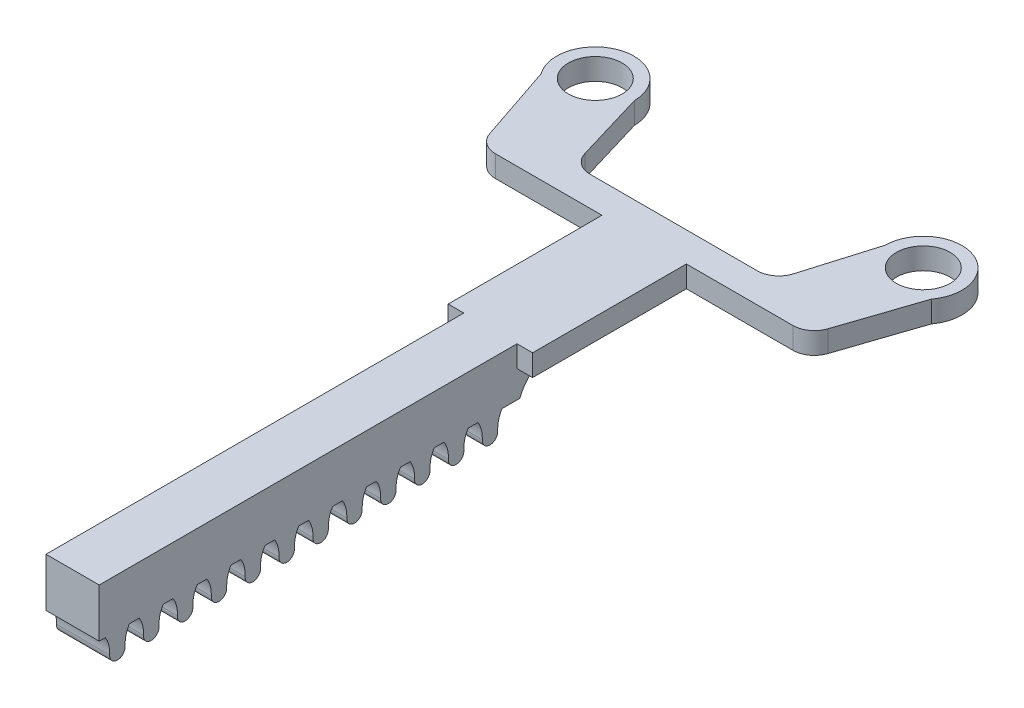
SolidWorks part; units mm, degrees
ref_plane "Front Plane" through (0, 0, 0) normal (0, 0, 1) x (1, 0, 0)
ref_plane "Top Plane" through (0, 0, 0) normal (0, 1, 0) x (1, 0, 0)
ref_plane "Right Plane" through (0, 0, 0) normal (1, 0, 0) x (0, 0, -1)
sketch "Sketch1" plane through (0, 0, 0) normal (0, 1, 0) x (1, 0, 0)
  line L0 (-0.29, 2.86) -> (-2.27, 2.86)
  line L1 (0.99, 0) -> (0.99, -7.77)
  line L2 (0, 0) -> (0, -7.77)
  line L3 (0, -7.77) -> (0.99, -7.77)
  line L4 (0.495, 0) -> (0.495, -7.77)
  line L5 (-0.29, 3.41) -> (1.28, 3.41)
  line L6 (-0.29, 2.86) -> (-0.29, 0)
  line L7 (-0.29, 0) -> (0, 0)
  line L8 (0.495, 3.41) -> (0.495, 0)
  line L9 (-0.29, 3.41) -> (0.495, 3.41)
  line L10 (1.28, 0) -> (0.99, 0)
  line L11 (1.28, 2.86) -> (1.28, 0)
  line L12 (0.495, 3.41) -> (0.495, 2.86)
  line L13 (-0.29, 3.41) -> (-1.06, 3.41)
  line L14 (1.28, 3.41) -> (2.05, 3.41)
  line L15 (-1.4433, 3.6956) -> (-1.8351, 5.0084)
  line L16 (1.28, 2.86) -> (3.26, 2.86)
  line L17 (-2.6491, 3.1324) -> (-3.1341, 4.5729)
  line L18 (3.6391, 3.1324) -> (4.1241, 4.5729)
  line L19 (2.4333, 3.6956) -> (2.8251, 5.0084)
  circle A0 centre (-2.5551, 5.0011) radius 0.5
  arc A1 (-1.8351, 5.0084) -> (-3.1341, 4.5729) centre (-2.5551, 5.0011) ccw
  arc A2 (-2.6491, 3.1324) -> (-2.27, 2.86) centre (-2.27, 3.26) ccw
  arc A3 (-1.4433, 3.6956) -> (-1.06, 3.41) centre (-1.06, 3.81) ccw
  arc A4 (2.4333, 3.6956) -> (2.05, 3.41) centre (2.05, 3.81) cw
  arc A5 (3.6391, 3.1324) -> (3.26, 2.86) centre (3.26, 3.26) cw
  arc A6 (2.8251, 5.0084) -> (4.1241, 4.5729) centre (3.5451, 5.0011) cw
  circle A7 centre (3.5451, 5.0011) radius 0.5
  point P16 (0, 0)
  point P17 (0, 0)
  dimension "D6" = 1.98
  dimension "D8" = 1.37
  dimension "D9" = 1.52
  dimension "D10" = 2.16
  dimension "D1" = 0.785
  dimension "D2" = 7.77
  dimension "D3" = 0.495
  dimension "D4" = 3.41
  dimension "D7" = 0.77
  dimension "D11" = 0.72
extrude "Boss-Extrude1" add sketch "Sketch1" along normal blind 0.4 contours A6 L19 A4 L14 L5 L8 L4 L3 L1 L10 L11 L16 A5 L18 A7 | A3 L15 A1 L17 A2 L0 L6 L7 L2 L3 L4 L8 L5 L13 A0
sketch "Sketch2" plane through (0, 0, 0) normal (0, -1, 0) x (1, 0, 0)
  line L1 (0.99, 7.77) -> (0, 7.77)
  line L2 (0.99, 7.77) -> (0.99, 0)
  line L3 (0.99, 0) -> (0, 0)
  line L4 (0, 7.77) -> (0, 0)
extrude "Boss-Extrude2" add sketch "Sketch2" along normal blind 1
sketch "Sketch4" plane through (0, 0, 0) normal (-1, 0, 0) x (0, 0, 1)
sketch "Sketch5" plane through (0, 0, 0) normal (-1, 0, 0) x (0, 0, 1)
  line L0 (7.2892, -0.8353) -> (7.2892, -0.4252) construction
  line L1 (7.2081, -0.5054) -> (6.7982, -0.5054)
  line L2 (7.6566, -0.5054) -> (7.7801, -0.5054)
  line L3 (7.0266, -0.5054) -> (7.1501, -0.5054)
  line L4 (6.5781, -0.5054) -> (6.4546, -0.5054)
  line L5 (6.3966, -0.5054) -> (6.5201, -0.5054)
  line L6 (5.9481, -0.5054) -> (5.8246, -0.5054)
  line L7 (5.7666, -0.5054) -> (5.8901, -0.5054)
  line L8 (5.3181, -0.5054) -> (5.1946, -0.5054)
  line L9 (5.1366, -0.5054) -> (5.2601, -0.5054)
  line L10 (4.6881, -0.5054) -> (4.5646, -0.5054)
  line L11 (4.5066, -0.5054) -> (4.6301, -0.5054)
  line L12 (4.0581, -0.5054) -> (3.9346, -0.5054)
  line L13 (3.8766, -0.5054) -> (4.0001, -0.5054)
  line L14 (3.4281, -0.5054) -> (3.3046, -0.5054)
  line L15 (3.2466, -0.5054) -> (3.3701, -0.5054)
  line L16 (2.7981, -0.5054) -> (2.6746, -0.5054)
  line L17 (2.6166, -0.5054) -> (2.7401, -0.5054)
  line L18 (2.1681, -0.5054) -> (2.0446, -0.5054)
  line L19 (1.9866, -0.5054) -> (2.1101, -0.5054)
  line L20 (1.5381, -0.5054) -> (1.4146, -0.5054)
  line L21 (1.3566, -0.5054) -> (1.4801, -0.5054)
  line L22 (0.9081, -0.5054) -> (0.7846, -0.5054)
  line L23 (0.7266, -0.5054) -> (0.8501, -0.5054)
  line L24 (0.2781, -0.5054) -> (0.1546, -0.5054)
  line L25 (7.7801, -0.5054) -> (7.9342, -1.2016)
  line L26 (7.9342, -1.2016) -> (-0.0987, -1.2016)
  line L27 (-0.0987, -1.2016) -> (0.1546, -0.5054)
  circle A0 centre (7.4324, -0.8353) radius 0.1432
  arc A1 (6.6596, -0.8245) -> (6.9451, -0.8245) centre (6.8024, -0.8353) ccw
  arc A2 (6.0296, -0.8245) -> (6.3151, -0.8245) centre (6.1724, -0.8353) ccw
  arc A3 (5.3996, -0.8245) -> (5.6851, -0.8245) centre (5.5424, -0.8353) ccw
  arc A4 (4.7696, -0.8245) -> (5.0551, -0.8245) centre (4.9124, -0.8353) ccw
  arc A5 (4.1396, -0.8245) -> (4.4251, -0.8245) centre (4.2824, -0.8353) ccw
  arc A6 (3.5096, -0.8245) -> (3.7951, -0.8245) centre (3.6524, -0.8353) ccw
  arc A7 (2.8796, -0.8245) -> (3.1651, -0.8245) centre (3.0224, -0.8353) ccw
  arc A8 (2.2496, -0.8245) -> (2.5351, -0.8245) centre (2.3924, -0.8353) ccw
  arc A9 (1.6196, -0.8245) -> (1.9051, -0.8245) centre (1.7624, -0.8353) ccw
  arc A10 (0.9896, -0.8245) -> (1.2751, -0.8245) centre (1.1324, -0.8353) ccw
  arc A11 (0.3596, -0.8245) -> (0.6451, -0.8245) centre (0.5024, -0.8353) ccw
  spline S0 degree 2 poles (7.2892, -0.8353) (7.2977, -0.6466) (7.2081, -0.5054) knots 0 0 0 0.769777 0.769777 0.769777
  spline S1 degree 2 poles (7.5755, -0.8353) (7.567, -0.6466) (7.6566, -0.5054) knots 0 0 0 0.769777 0.769777 0.769777
  spline S2 degree 2 poles (6.6592, -0.8353) (6.6677, -0.6466) (6.5781, -0.5054) knots 0 0 0 0.769777 0.769777 0.769777
  spline S3 degree 2 poles (6.9455, -0.8353) (6.937, -0.6466) (7.0266, -0.5054) knots 0 0 0 0.769777 0.769777 0.769777
  spline S4 degree 2 poles (6.0292, -0.8353) (6.0377, -0.6466) (5.9481, -0.5054) knots 0 0 0 0.769777 0.769777 0.769777
  spline S5 degree 2 poles (6.3155, -0.8353) (6.307, -0.6466) (6.3966, -0.5054) knots 0 0 0 0.769777 0.769777 0.769777
  spline S6 degree 2 poles (5.3992, -0.8353) (5.4077, -0.6466) (5.3181, -0.5054) knots 0 0 0 0.769777 0.769777 0.769777
  spline S7 degree 2 poles (5.6855, -0.8353) (5.677, -0.6466) (5.7666, -0.5054) knots 0 0 0 0.769777 0.769777 0.769777
  spline S8 degree 2 poles (4.7692, -0.8353) (4.7777, -0.6466) (4.6881, -0.5054) knots 0 0 0 0.769777 0.769777 0.769777
  spline S9 degree 2 poles (5.0555, -0.8353) (5.047, -0.6466) (5.1366, -0.5054) knots 0 0 0 0.769777 0.769777 0.769777
  spline S10 degree 2 poles (4.1392, -0.8353) (4.1477, -0.6466) (4.0581, -0.5054) knots 0 0 0 0.769777 0.769777 0.769777
  spline S11 degree 2 poles (4.4255, -0.8353) (4.417, -0.6466) (4.5066, -0.5054) knots 0 0 0 0.769777 0.769777 0.769777
  spline S12 degree 2 poles (3.5092, -0.8353) (3.5177, -0.6466) (3.4281, -0.5054) knots 0 0 0 0.769777 0.769777 0.769777
  spline S13 degree 2 poles (3.7955, -0.8353) (3.787, -0.6466) (3.8766, -0.5054) knots 0 0 0 0.769777 0.769777 0.769777
  spline S14 degree 2 poles (2.8792, -0.8353) (2.8877, -0.6466) (2.7981, -0.5054) knots 0 0 0 0.769777 0.769777 0.769777
  spline S15 degree 2 poles (3.1655, -0.8353) (3.157, -0.6466) (3.2466, -0.5054) knots 0 0 0 0.769777 0.769777 0.769777
  spline S16 degree 2 poles (2.2492, -0.8353) (2.2577, -0.6466) (2.1681, -0.5054) knots 0 0 0 0.769777 0.769777 0.769777
  spline S17 degree 2 poles (2.5355, -0.8353) (2.527, -0.6466) (2.6166, -0.5054) knots 0 0 0 0.769777 0.769777 0.769777
  spline S18 degree 2 poles (1.6192, -0.8353) (1.6277, -0.6466) (1.5381, -0.5054) knots 0 0 0 0.769777 0.769777 0.769777
  spline S19 degree 2 poles (1.9055, -0.8353) (1.897, -0.6466) (1.9866, -0.5054) knots 0 0 0 0.769777 0.769777 0.769777
  spline S20 degree 2 poles (0.9892, -0.8353) (0.9977, -0.6466) (0.9081, -0.5054) knots 0 0 0 0.769777 0.769777 0.769777
  spline S21 degree 2 poles (1.2755, -0.8353) (1.267, -0.6466) (1.3566, -0.5054) knots 0 0 0 0.769777 0.769777 0.769777
  spline S22 degree 2 poles (0.3592, -0.8353) (0.3677, -0.6466) (0.2781, -0.5054) knots 0 0 0 0.769777 0.769777 0.769777
  spline S23 degree 2 poles (0.6455, -0.8353) (0.637, -0.6466) (0.7266, -0.5054) knots 0 0 0 0.769777 0.769777 0.769777
  point P5 (0, 0)
  point P8 (0, 0)
  point P113 (0, 0)
extrude "Cut-Extrude1" cut sketch "Sketch5" against normal blind 1 contours A0 L0 S0 L1 S3 A1 S2 L4 L5 S5 A2 S4 L6 L7 S7 A3 S6 L8 L9 S9 A4 S8 L10 L11 S11 A5 S10 L12 L13 S13 A6 S12 L14
sketch "Sketch6" plane through (0, 0, 0) normal (0, -1, 0) x (1, 0, 0)
  line L1 (0.99, 0) -> (0, 0)
  line L2 (0.99, 0) -> (0.99, -0.8)
  line L3 (0.99, -0.8) -> (0, -0.8)
  line L4 (0, 0) -> (0, -0.8)
  dimension "D1" = 0.99
  dimension "D2" = 0.8
extrude "Boss-Extrude3" add sketch "Sketch6" along normal blind 1
sketch "Sketch7" plane through (0, 0, 0) normal (-1, 0, 0) x (0, 0, 1)
  line L0 (0, 0) -> (-0.8, 0) construction
  circle A0 centre (-0.8, -0.8091) radius 0.8091
extrude "Cut-Extrude3" cut sketch "Sketch7" against normal blind 1
sketch "Sketch8" plane through (0, 0, 0) normal (-1, 0, 0) x (0, 0, 1)
  line L0 (0, -1) -> (-0.0137, -1)
  line L1 (-0.0137, -1) -> (0, -0.9303)
  line L2 (0, -0.9303) -> (0, -1)
extrude "Cut-Extrude4" cut sketch "Sketch8" against normal blind 1
sketch "Sketch9" plane through (0, 0, 0) normal (-1, 0, 0) x (0, 0, 1)
  line L0 (0.1546, -0.5054) -> (-0.05, -0.5054)
  line L1 (-0.05, -0.5054) -> (0, -0.9303)
  line L2 (0, -0.9303) -> (0.1546, -0.5054)
  arc A0 (0, -0.9303) -> (-0.8, 0) centre (-0.8, -0.8091) ccw construction
extrude "Cut-Extrude5" cut sketch "Sketch9" against normal blind 1
